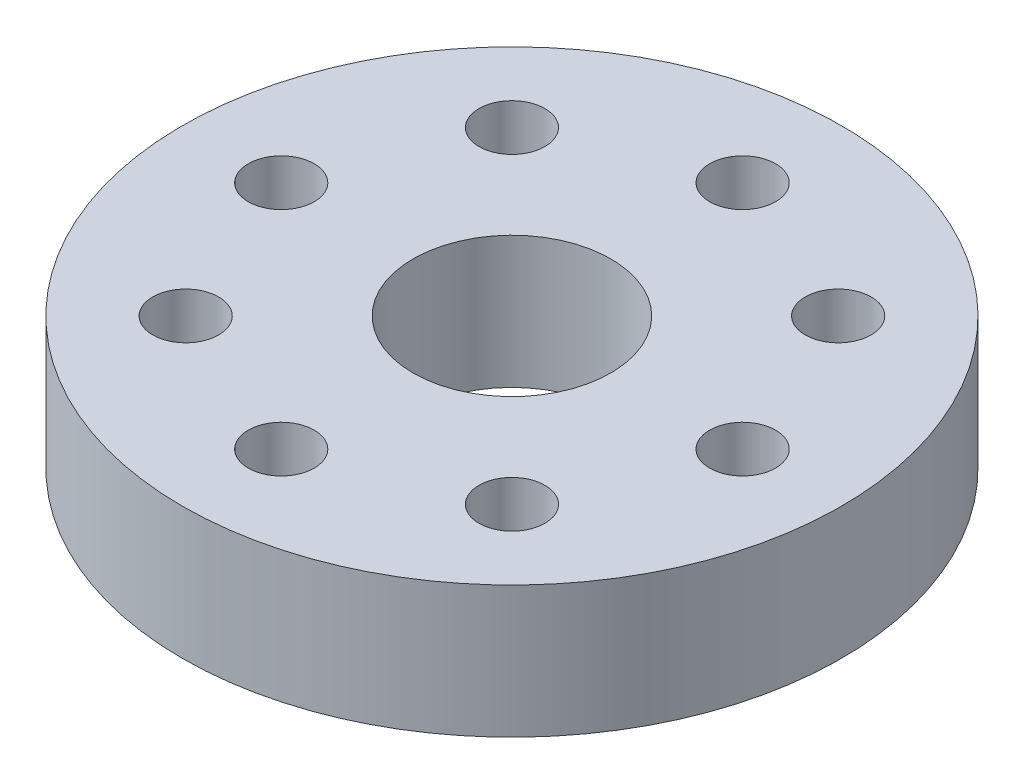
SolidWorks part; units mm, degrees
material "3003 Alloy"
ref_plane "Front Plane" through (0, 0, 0) normal (0, 0, 1) x (1, 0, 0)
ref_plane "Top Plane" through (0, 0, 0) normal (0, 1, 0) x (1, 0, 0)
ref_plane "Right Plane" through (0, 0, 0) normal (1, 0, 0) x (0, 0, -1)
sketch "Sketch2" plane through (0, 0, 0) normal (0, 1, 0) x (1, 0, 0)
  line L0 (-10.9846, 0) -> (10.9846, 0) construction
  line L1 (0, 5.6811) -> (0, -5.6811) construction
  circle A0 centre (0, 0) radius 10
  circle A1 centre (0, 0) radius 3
  circle A2 centre (0, 7) radius 1
  circle A3 centre (4.9497, 4.9497) radius 1
  circle A4 centre (7, 0) radius 1
  circle A5 centre (4.9497, -4.9497) radius 1
  circle A6 centre (0, -7) radius 1
  circle A7 centre (-4.9497, -4.9497) radius 1
  circle A8 centre (-7, 0) radius 1
  circle A9 centre (-4.9497, 4.9497) radius 1
  point P27 (0, 0)
  dimension "D1" = 20
  dimension "D2" = 6
  dimension "D4" = 2
  dimension "D3" = 7
  dimension "D5" = 8
extrude "Boss-Extrude1" add sketch "Sketch2" along normal blind 4
